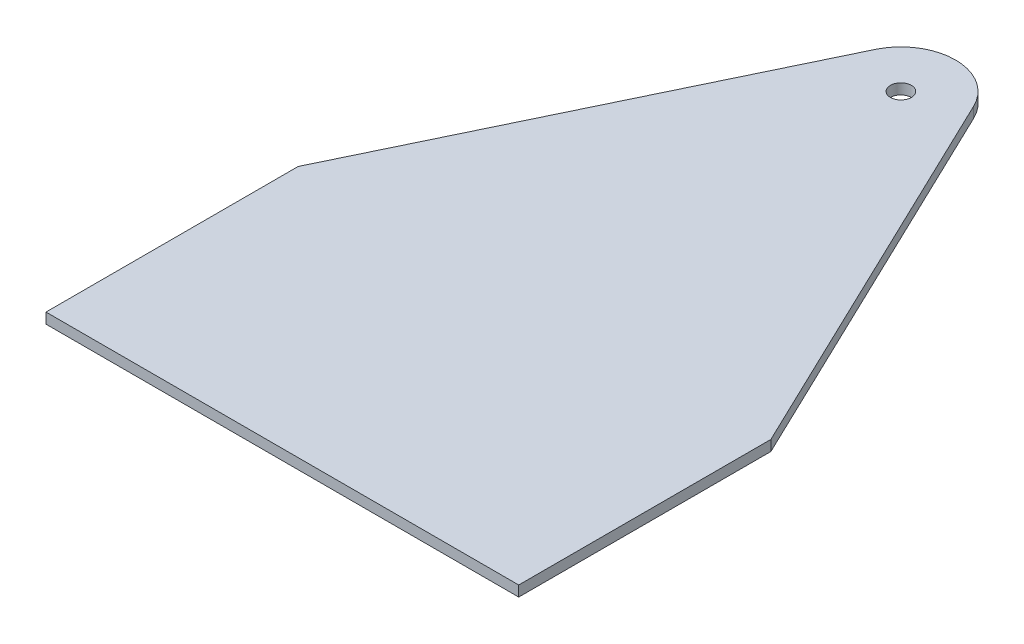
SolidWorks part; units mm, degrees
ref_plane "Front Plane" through (0, 0, 0) normal (0, 0, 1) x (1, 0, 0)
ref_plane "Top Plane" through (0, 0, 0) normal (0, 1, 0) x (1, 0, 0)
ref_plane "Right Plane" through (0, 0, 0) normal (1, 0, 0) x (0, 0, -1)
sketch "Sketch1" plane through (0, 0, 0) normal (0, 1, 0) x (1, 0, 0)
  line L0 (-71.4375, 0) -> (71.4375, 0)
  line L1 (-71.4375, 38.1) -> (71.4375, 38.1) construction
  line L2 (-71.4375, 0) -> (-71.4375, 76.2)
  line L3 (-71.4375, 38.1) -> (0, 186.9445) construction
  line L8 (0, 186.9445) -> (71.4375, 38.1) construction
  line L13 (71.4375, 0) -> (71.4375, 76.2)
  line L14 (-71.4375, 76.2) -> (-14.8624, 194.0777)
  line L15 (14.8624, 194.0777) -> (71.4375, 76.2)
  arc A0 (-14.8624, 194.0777) -> (14.8624, 194.0777) centre (0, 186.9445) cw
  circle A1 centre (0, 186.9445) radius 3.175
  point P4 (0, 0)
  dimension "D5" = 6.35
  dimension "D1" = 142.875
  dimension "D2" = 165.1
  dimension "D3" = 38.1
  dimension "D4" = 76.2
extrude "Boss-Extrude1" add sketch "Sketch1" along normal blind 3.175
